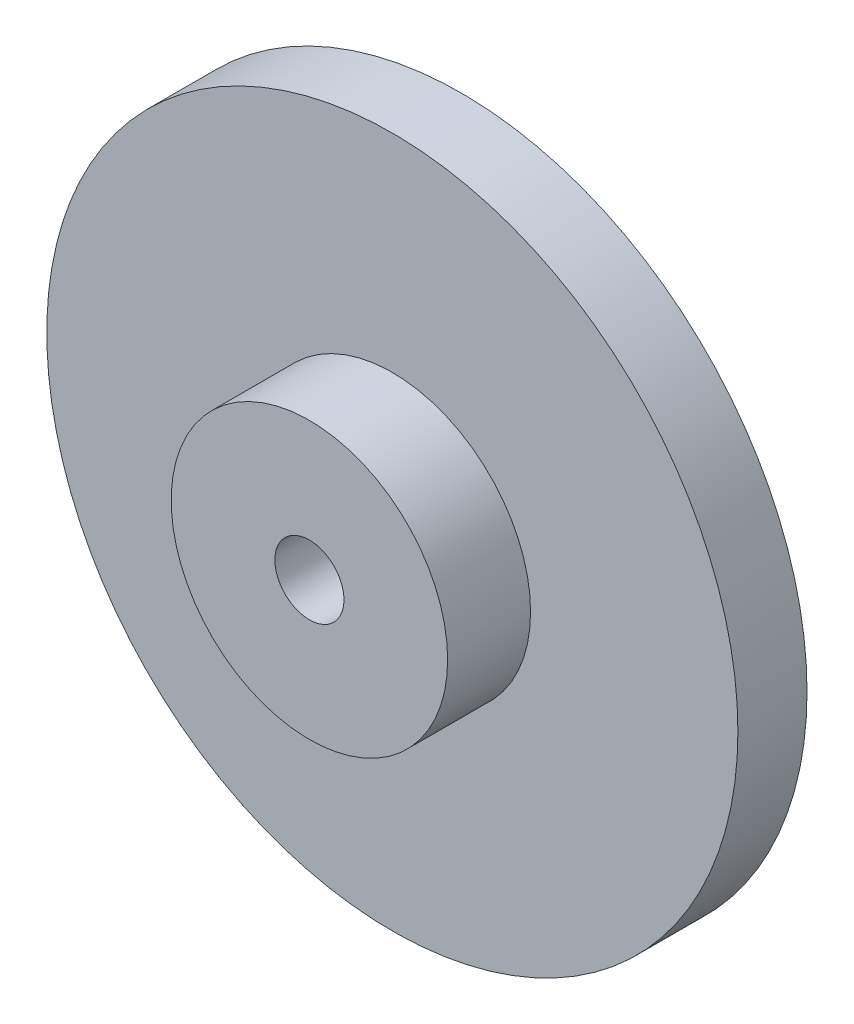
SolidWorks part; units mm, degrees
ref_plane "Plan de face" through (0, 0, 0) normal (0, 0, 1) x (1, 0, 0)
ref_plane "Plan de dessus" through (0, 0, 0) normal (0, 1, 0) x (1, 0, 0)
ref_plane "Plan de droite" through (0, 0, 0) normal (1, 0, 0) x (0, 0, -1)
sketch "Esquisse1" plane through (0, 0, 0) normal (0, 0, 1) x (1, 0, 0)
  circle A0 centre (0, 0) radius 25
  dimension "D1" = 50
extrude "Boss.-Extru.1" add sketch "Esquisse1" along normal blind 5
sketch "Esquisse2" plane through (0, 0, 5) normal (0, 0, 1) x (1, 0, 0)
  circle A0 centre (0, 0) radius 10
  dimension "D1" = 20
extrude "Boss.-Extru.2" add sketch "Esquisse2" along normal blind 6
sketch "Esquisse3" plane through (0, 0, 11) normal (0, 0, 1) x (1, 0, 0)
  circle A0 centre (0, 0) radius 2.5
  dimension "D1" = 5
extrude "Enlèv. mat.-Extru.1" cut sketch "Esquisse3" against normal through all
